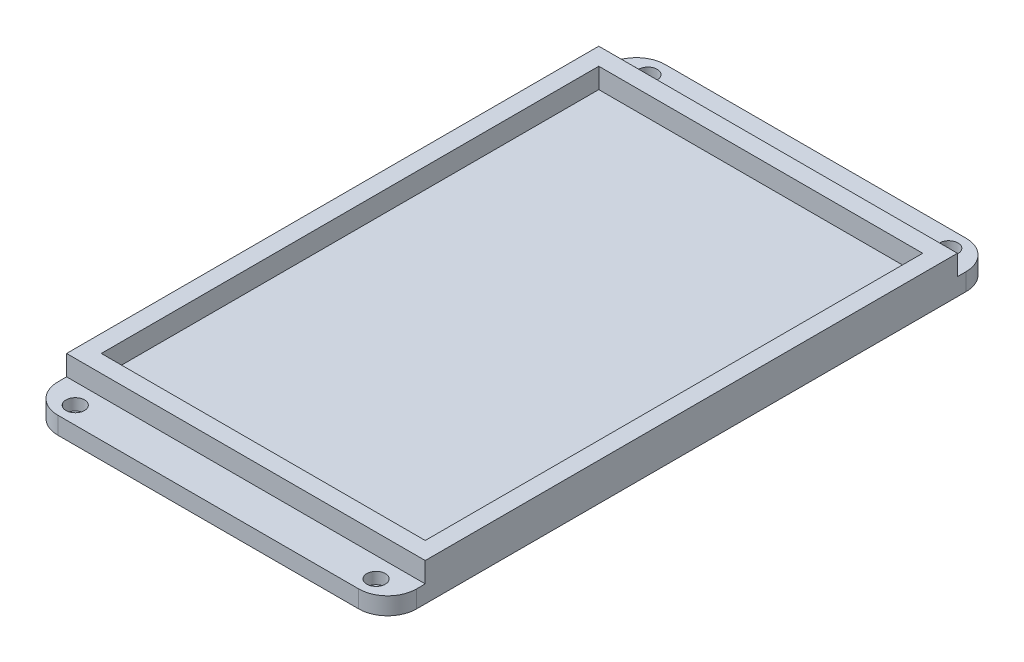
SolidWorks part; units mm, degrees
ref_plane "前视基准面" through (0, 0, 0) normal (0, 0, 1) x (1, 0, 0)
ref_plane "上视基准面" through (0, 0, 0) normal (0, 1, 0) x (1, 0, 0)
ref_plane "右视基准面" through (0, 0, 0) normal (1, 0, 0) x (0, 0, -1)
other "Configuration Table"
sketch "草图1" plane through (0, 0, 0) normal (0, 1, 0) x (1, 0, 0)
  line L1 (-28, -43) -> (28, -43)
  line L2 (-28, -43) -> (-28, 43)
  line L3 (-28, 43) -> (28, 43)
  line L4 (28, -43) -> (28, 43)
  line L5 (-28, -43) -> (28, 43) construction
  line L6 (-28, 43) -> (28, -43) construction
  line L7 (-31, -46) -> (31, -46)
  line L8 (-31, -46) -> (-31, 46)
  line L9 (-31, 46) -> (31, 46)
  line L10 (31, -46) -> (31, 46)
  line L11 (-31, -46) -> (31, 46) construction
  line L12 (-31, 46) -> (31, -46) construction
  point P0 (0, 0)
  point P6 (0, 0)
  dimension "D1" = 56
  dimension "D2" = 86
  dimension "D3" = 3
  dimension "D4" = 3
extrude "凸台-拉伸1" add sketch "草图1" along normal blind 3.5
sketch "草图2" plane through (0, 0, 0) normal (0, -1, 0) x (1, 0, 0)
  line L1 (-31, -52.5) -> (31, -52.5)
  line L2 (-31, -52.5) -> (-31, 52.5)
  line L3 (-31, 52.5) -> (31, 52.5)
  line L4 (31, -52.5) -> (31, 52.5)
  line L5 (-31, -52.5) -> (31, 52.5) construction
  line L6 (-31, 52.5) -> (31, -52.5) construction
  point P0 (0, 0)
  dimension "D1" = 62
  dimension "D2" = 105
extrude "凸台-拉伸2" add sketch "草图2" along normal blind 3
fillet "圆角2" radius 5 4 edges at (31, -1.5, -52.5) (-31, -1.5, -52.5) (-31, -1.5, 52.5) (31, -1.5, 52.5)
sketch "草图3" plane through (0, 0, 0) normal (0, 1, 0) x (1, 0, 0)
  line L0 (0, 69.2966) -> (0, -61.4932) construction
  line L1 (-26, 52.5) -> (26, 52.5) construction
  line L2 (-31, 46) -> (-31, 47.5) construction
  line L3 (-1.925, 0) -> (1.925, 0) construction
  circle A0 centre (-26, 49.5) radius 1.6
  circle A1 centre (26, 49.5) radius 1.6
  circle A2 centre (26, -49.5) radius 1.6
  circle A3 centre (-26, -49.5) radius 1.6
  dimension "D1" = 3.2
  dimension "D2" = 3
  dimension "D3" = 5
extrude "切除-拉伸1" cut sketch "草图3" against normal blind 2
